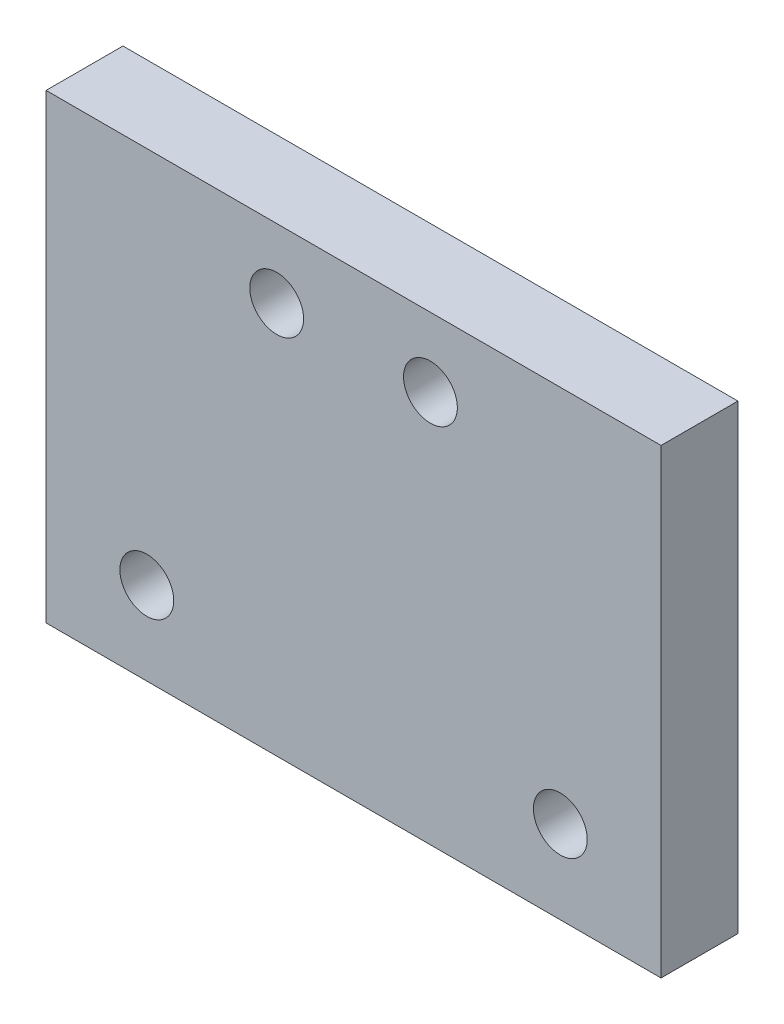
SolidWorks part; units mm, degrees
ref_plane "Front Plane" through (0, 0, 0) normal (0, 0, 1) x (1, 0, 0)
ref_plane "Top Plane" through (0, 0, 0) normal (0, 1, 0) x (1, 0, 0)
ref_plane "Right Plane" through (0, 0, 0) normal (1, 0, 0) x (0, 0, -1)
sketch "Sketch1" plane through (0, 0, 0) normal (0, 0, 1) x (1, 0, 0)
  line L0 (20, 40.6636) -> (20, -13.3744) construction
  line L1 (0, 0) -> (40, 0)
  line L2 (0, 0) -> (0, 30)
  line L3 (0, 30) -> (40, 30)
  line L4 (40, 0) -> (40, 30)
  line L5 (-14.837, 15) -> (59.4465, 15) construction
  circle A0 centre (15, 25.5) radius 1.75
  circle A1 centre (25, 25.5) radius 1.75
  circle A2 centre (6.55, 5.4) radius 1.75
  circle A3 centre (33.45, 5.4) radius 1.75
  dimension "D4" = 3.5
  dimension "D6" = 3.5
  dimension "D1" = 40
  dimension "D2" = 30
  dimension "D3" = 20
  dimension "D5" = 10
  dimension "D7" = 26.9
  dimension "D8" = 20.1
  dimension "D9" = 15
  dimension "D10" = 10.5
extrude "Boss-Extrude1" add sketch "Sketch1" against normal blind 5
